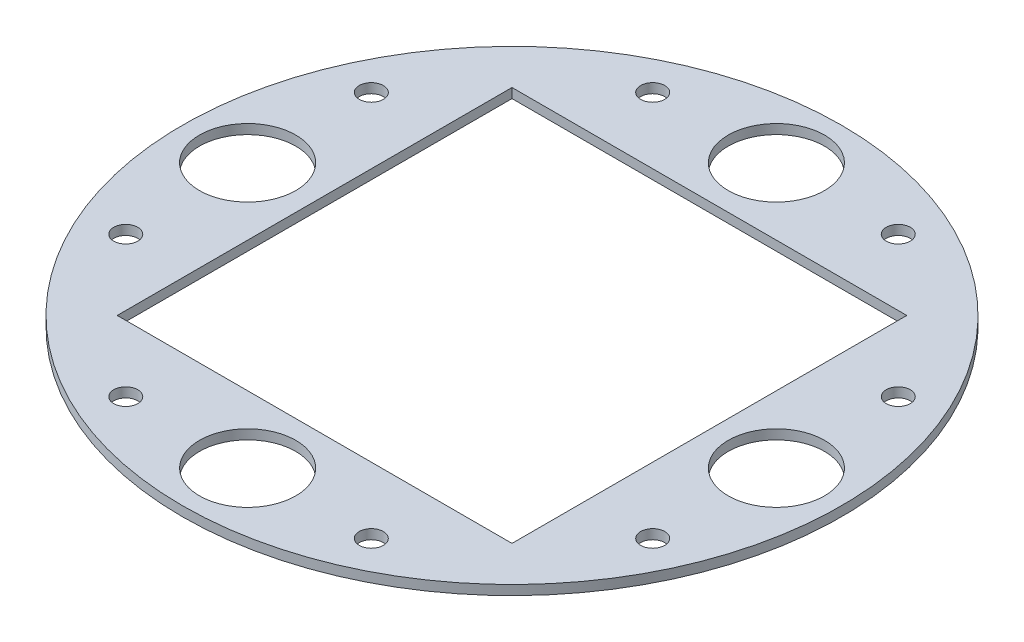
SolidWorks part; units mm, degrees
ref_plane "Front Plane" through (0, 0, 0) normal (0, 0, 1) x (1, 0, 0)
ref_plane "Top Plane" through (0, 0, 0) normal (0, 1, 0) x (1, 0, 0)
ref_plane "Right Plane" through (0, 0, 0) normal (1, 0, 0) x (0, 0, -1)
sketch "Sketch1" plane through (0, 0, 0) normal (0, 1, 0) x (1, 0, 0)
  circle A0 centre (0, 0) radius 86.9315
extrude "Boss-Extrude1" add sketch "Sketch1" along normal blind 2.54
sketch "Sketch3" plane through (0, 2.54, 0) normal (0, 1, 0) x (1, 0, 0)
  line L1 (-52.07, 52.07) -> (52.07, 52.07)
  line L2 (-52.07, 52.07) -> (-52.07, -52.07)
  line L3 (-52.07, -52.07) -> (52.07, -52.07)
  line L4 (52.07, 52.07) -> (52.07, -52.07)
  line L5 (-52.07, 52.07) -> (52.07, -52.07) construction
  line L6 (-52.07, -52.07) -> (52.07, 52.07) construction
  point P0 (0, 0)
extrude "Cut-Extrude2" cut sketch "Sketch3" against normal blind 2.54
sketch "Sketch4" plane through (0, 2.54, 0) normal (0, 1, 0) x (1, 0, 0)
  line L0 (0, 86.9315) -> (0, -86.9315) construction
  line L1 (86.9315, 0) -> (-86.9315, 0)
  line L2 (-0.0868, 0.0745) -> (0, 0)
  circle A0 centre (-32.385, 69.5007) radius 3.175
  circle A1 centre (32.385, 69.5007) radius 3.175
  circle A2 centre (69.5007, 32.385) radius 3.175
  circle A3 centre (69.5007, -32.385) radius 3.175
  circle A4 centre (32.385, -69.5007) radius 3.175
  circle A5 centre (-32.385, -69.5007) radius 3.175
  circle A6 centre (-69.5007, -32.385) radius 3.175
  circle A7 centre (-69.5007, 32.385) radius 3.175
  point P4 (0, 0)
extrude "Cut-Extrude3" cut sketch "Sketch4" against normal blind 2.54 contours A5 | A6 | A2 | A7 | A0 | A1 | A3 | A4
sketch "Sketch5" plane through (0, 2.54, 0) normal (0, 1, 0) x (1, 0, 0)
  line L0 (-52.07, 0) -> (-69.7384, 0)
  line L1 (-52.07, 52.07) -> (-52.07, -52.07) construction
  circle A0 centre (-69.7384, 0) radius 12.7
  dimension "D1" = 25.4
extrude "Cut-Extrude4" cut sketch "Sketch5" against normal through all contours A0
pattern_circular "CirPattern1" count 4 over 360 about axis through (0, 0, 0) along (0, 1, 0) of "Cut-Extrude4"
